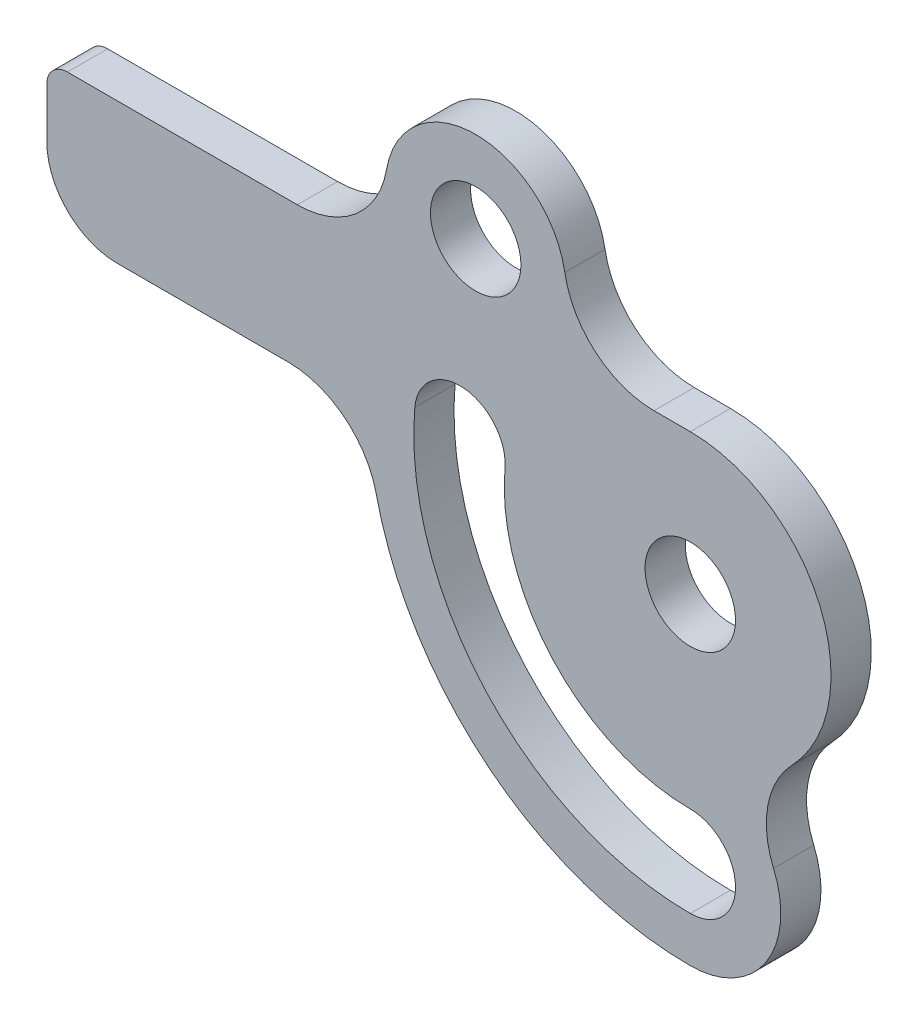
SolidWorks part; units mm, degrees
ref_plane "Front Plane" through (0, 0, 0) normal (0, 0, 1) x (1, 0, 0)
ref_plane "Top Plane" through (0, 0, 0) normal (0, 1, 0) x (1, 0, 0)
ref_plane "Right Plane" through (0, 0, 0) normal (1, 0, 0) x (0, 0, -1)
sketch "Sketch1" plane through (0, 0, 0) normal (0, 0, 1) x (1, 0, 0)
  line L14 (5.5563, 0) -> (19.8437, 0)
  line L15 (0, 5.5562) -> (25.4, 5.5562)
  line L16 (25.4, 5.5562) -> (25.4, -5.5562) construction
  line L18 (16.3066, 0.7956) -> (25.4, 0) construction
  line L19 (25.4, 0) -> (25.4, -9.1281) construction
  line L20 (5.5563, 0) -> (0, 0)
  line L21 (0, 0) -> (0, 5.5562)
  line L22 (16.9292, 7.9121) -> (16.3066, 0.7956) construction
  circle A32 centre (0, 0) radius 5.5563 construction
  circle A33 centre (25.4, 0) radius 5.5563 construction
  circle A34 centre (25.4, -9.1281) radius 3.5719
  arc A35 (25.4, -5.5562) -> (25.4, 5.5562) centre (25.4, 0) ccw
  circle A36 centre (25.4, 0) radius 1.7859
  circle A37 centre (25.4, -9.1281) radius 1.7859
  arc A38 (19.8437, 0) -> (25.4, -5.5562) centre (25.4, 0) ccw
  circle A39 centre (25.4, 0) radius 9.1281 construction
  circle A40 centre (2.7781, 2.7781) radius 2.7781
  circle A41 centre (0.8137, 4.7426) radius 0.8137
  circle A42 centre (16.3066, 0.7956) radius 1.7859
  circle A43 centre (16.3066, 0.7956) radius 3.5719 construction
  circle A44 centre (16.9292, 7.9121) radius 1.7859
  circle A45 centre (16.9292, 7.9121) radius 3.5719
  arc A46 (18.0858, 0.6399) -> (25.4, -7.3422) centre (25.4, 0) ccw
  arc A47 (25.4, -10.9141) -> (14.5275, 0.9512) centre (25.4, 0) cw
  arc A48 (25.4, -12.7) -> (12.7483, 1.1069) centre (25.4, 0) cw
  point P0 (0, 0)
  dimension "D8" = 25.4
  dimension "D9" = 11.1125
  dimension "D10" = 3.5719
  dimension "D11" = 7.1437
  dimension "D12" = 95
extrude "Boss-Extrude1" add sketch "Sketch1" along normal blind 1.5875
fillet "Fillet1" radius 3.5719 4 edges at (25.4, -5.5562, 0.7937) (14.2444, 5.5562, 0.7937) (19.614, 5.5562, 0.7937) (12.7, 0, 0.7937)
